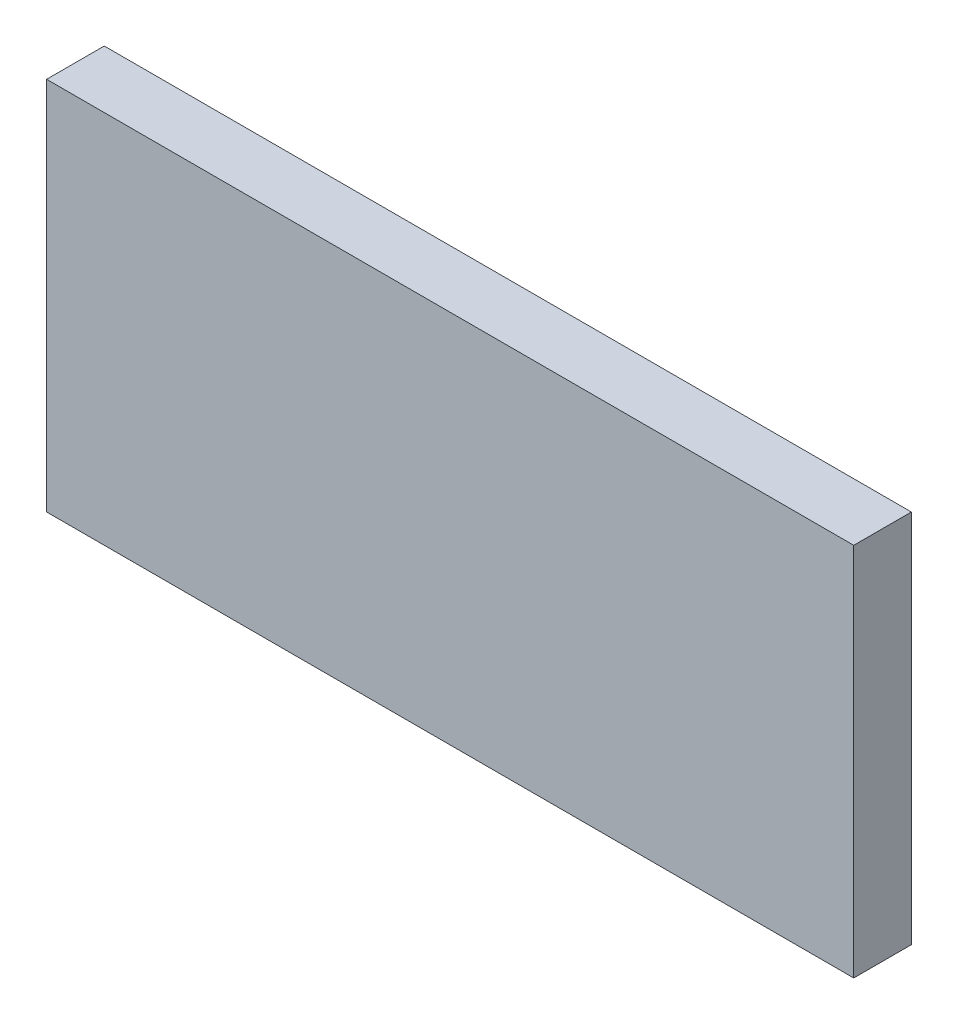
SolidWorks part; units mm, degrees
ref_plane "Plan de face" through (0, 0, 0) normal (0, 0, 1) x (1, 0, 0)
ref_plane "Plan de dessus" through (0, 0, 0) normal (0, 1, 0) x (1, 0, 0)
ref_plane "Plan de droite" through (0, 0, 0) normal (1, 0, 0) x (0, 0, -1)
sketch "Esquisse1" plane through (0, 0, 0) normal (0, 0, 1) x (1, 0, 0)
  line L1 (-88.9, 41.275) -> (88.9, 41.275)
  line L2 (-88.9, 41.275) -> (-88.9, -41.275)
  line L3 (-88.9, -41.275) -> (88.9, -41.275)
  line L4 (88.9, 41.275) -> (88.9, -41.275)
  line L5 (-88.9, 41.275) -> (88.9, -41.275) construction
  line L6 (-88.9, -41.275) -> (88.9, 41.275) construction
  point P0 (0, 0)
  dimension "D1" = 82.55
  dimension "D2" = 177.8
extrude "Boss.-Extru.1" add sketch "Esquisse1" along normal blind 12.7
